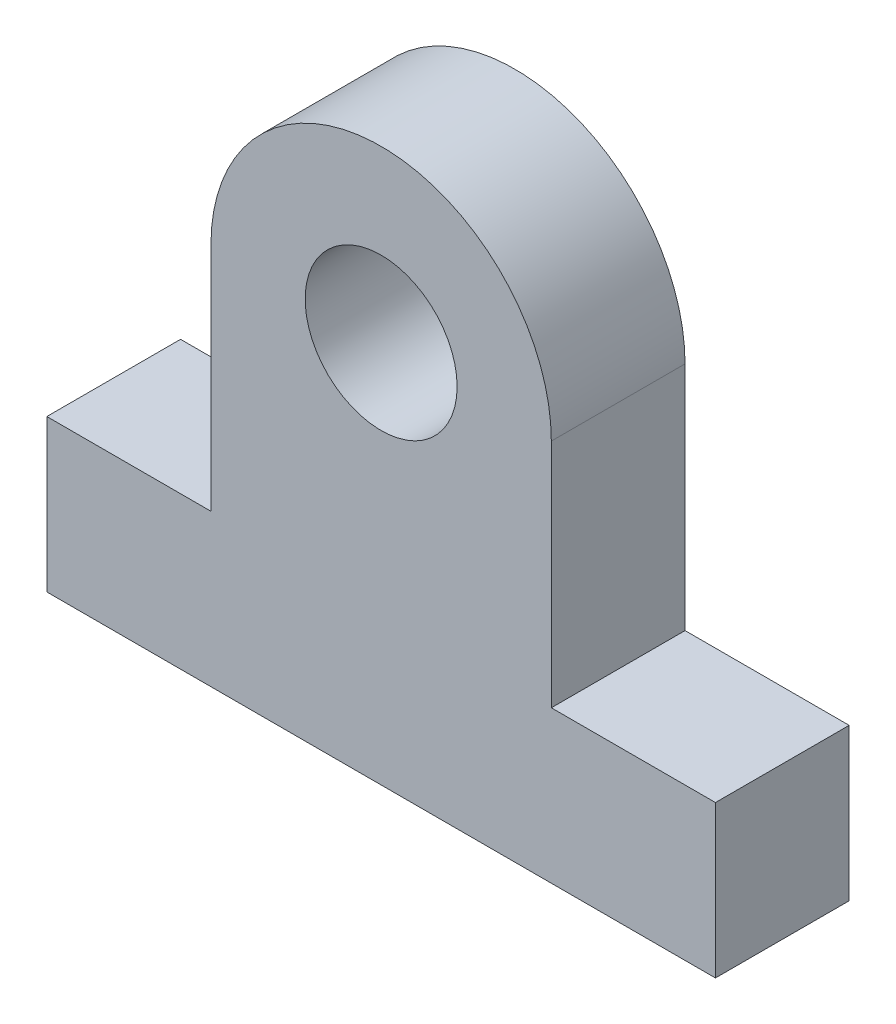
SolidWorks part; units mm, degrees
material "Plain Carbon Steel"
ref_plane "Front Plane" through (0, 0, 0) normal (0, 0, 1) x (1, 0, 0)
ref_plane "Top Plane" through (0, 0, 0) normal (0, 1, 0) x (1, 0, 0)
ref_plane "Right Plane" through (0, 0, 0) normal (1, 0, 0) x (0, 0, -1)
sketch "Sketch1" plane through (0, 0, 0) normal (0, 0, 1) x (1, 0, 0)
  line L0 (-55, 0) -> (55, 0)
  line L1 (55, 0) -> (55, 25)
  line L2 (55, 25) -> (-55, 25) construction
  line L3 (-55, 0) -> (-55, 25)
  line L4 (0, 25) -> (0, 219.9692) construction
  line L5 (-28, 25) -> (-28, 63)
  line L6 (28, 25) -> (28, 63)
  line L7 (-55, 25) -> (-28, 25)
  line L8 (28, 25) -> (55, 25)
  arc A0 (-28, 63) -> (28, 63) centre (0, 63) cw
  circle A1 centre (0, 63) radius 12.5
  dimension "D3" = 28
  dimension "D4" = 25
  dimension "D1" = 25
  dimension "D2" = 110
  dimension "D5" = 38
extrude "Boss-Extrude1" add sketch "Sketch1" along normal mid plane 22
